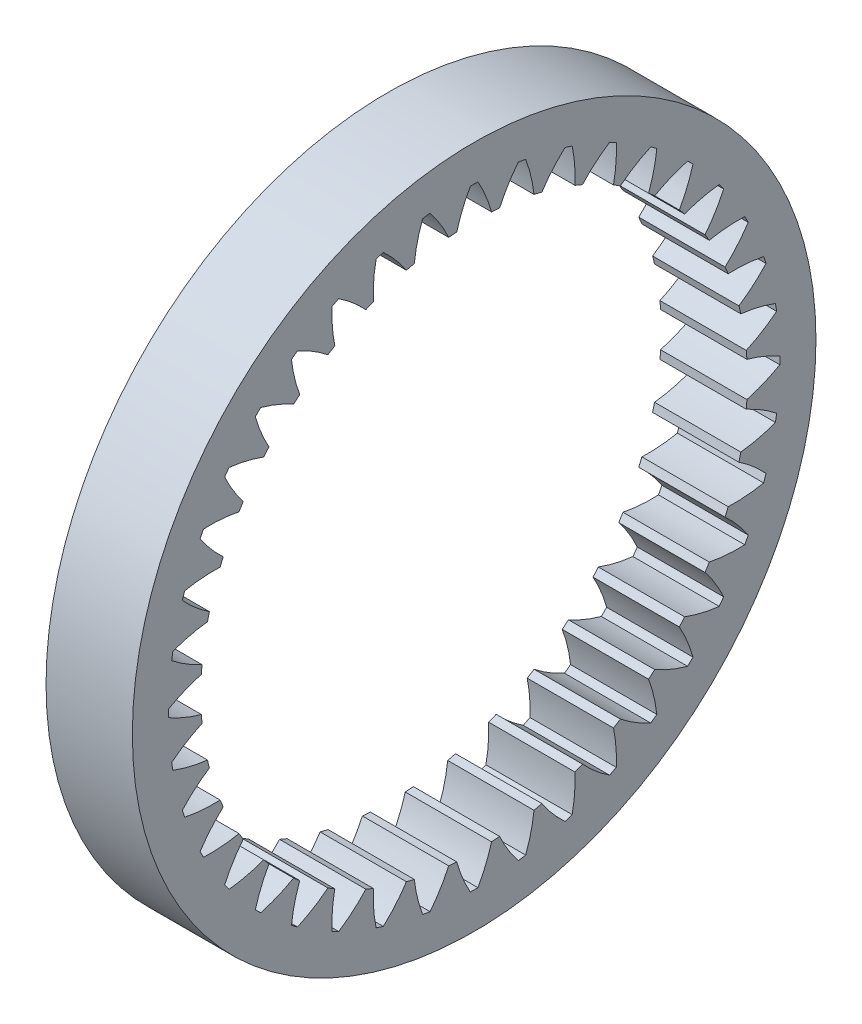
SolidWorks part; units mm, degrees
ref_plane "Plane1" through (0, 0, 0) normal (0, 0, 1) x (1, 0, 0)
ref_plane "Plane2" through (0, 0, 0) normal (0, 1, 0) x (1, 0, 0)
ref_plane "Plane3" through (0, 0, 0) normal (1, 0, 0) x (0, 0, -1)
sketch "HoldingSke" plane through (0, 0, 0) normal (0, 1, 0) x (1, 0, 0)
  line L0 (0, 0) -> (0.383, -0.3214)
  line L1 (-15, 0) -> (100, 0) construction
  line L2 (0, 0) -> (-2.1039, 2.3779)
  line L3 (0, 0) -> (-11.863, 4.5341)
  line L4 (0, 0) -> (6.6156, 5.5511)
  line L5 (0, 0) -> (-23.7986, -8.8762)
  line L6 (0, 0) -> (-10.5278, -7.1032)
  line L7 (-2.1039, 2.3779) -> (3.3635, 27.1825)
  line L8 (-76.2, 4.3779) -> (-54.61, 4.3779)
  line L9 (-71.009, 38.7566) -> (-53.1078, 45.2721)
  line L10 (-76.2, 71.12) -> (104.1128, 71.12)
  line L11 (0, 0) -> (-12, 0)
  line L12 (-76.2, 101.6) -> (-76.133, 101.6)
  line L13 (24.9733, 27.94) -> (52.9518, 28.4284)
  line L14 (24.9733, 27.94) -> (24.9743, 27.94)
  line L15 (24.9733, 27.94) -> (100.4006, 29.5858)
  circle A0 centre (0, 0) radius 12.5
  circle A1 centre (0, 0) radius 12.7
  circle A2 centre (0, 0) radius 12.7
  dimension "MHD" = 25.4
  dimension "Hub_dia" = 25.4
  dimension "Diameter" = 25
  dimension "Num_teeth" = 40
  dimension "Pitch" = 0.5
  dimension "Overall_len" = 25.4
  dimension "Show_teeth" = 40
  dimension "Thickness" = 12.7
  dimension "OAL" = 25.4001
  dimension "T_dim" = 21.59
  dimension "Ap" = 20
  dimension "H" = 19.05
  dimension "Pitch_radius" = 180.3128
  dimension "Width" = 12
  dimension "Backlash" = 0.067
  dimension "Addendum_fac" = 1
  dimension "Dedendum_fac" = 1.25
  dimension "Clearance_fac" = 0.25
  dimension "Dedendum_add" = 0.001
  dimension "Module" = 2
sketch "BasProSke" plane through (0, 0, 0) normal (0, 1, 0) x (1, 0, 0)
  line L0 (-10, 0) -> (60, 0) construction
  line L1 (0, 38) -> (0, 42.5264)
  line L2 (0, 38) -> (12, 38)
  line L3 (12, 38) -> (12, 42.5264)
  line L4 (12, 42.5264) -> (0, 42.5264)
  dimension "Thickness" = 12
  dimension "Diameter" = 85.0528
  dimension "Inside_diameter" = 76
revolve "Base-Revolve" add sketch "BasProSke" angle 360 about L0
sketch "TooCutSke" plane through (0, 0, 0) normal (1, 0, 0) x (0, 0, -1)
  line L3 (1.7379, 39.9622) -> (1.7379, 53.6633) construction
  line L4 (0, 0) -> (0, 59.563) construction
  line L5 (0, 0) -> (-5.3609, 68.1169) construction
  line L6 (-16.8604, 32.6066) -> (35.072, 36.6938) construction
  circle A0 centre (0, 0) radius 40 construction
  circle A1 centre (0, 0) radius 42.501 construction
  circle A2 centre (0, 0) radius 33.8289 construction
  circle A3 centre (0, 0) radius 37.9746 construction
  arc A4 (2.4273, 37.8969) -> (0.5225, 42.4978) centre (-16.8604, 32.6066) ccw
  arc A5 (2.4273, 37.8969) -> (-2.4273, 37.8969) centre (0, 0) ccw
  arc A6 (0.5225, 42.4978) -> (-0.5225, 42.4978) centre (0, 0) ccw
  arc A7 (-0.5225, 42.4978) -> (-2.4273, 37.8969) centre (16.8604, 32.6066) ccw
  dimension "Pitch_dia" = 80
  dimension "Base_dia" = 67.6579
  dimension "Root_dia" = 85.002
  dimension "Overcut_dia" = 75.9492
  dimension "Flank_rad" = 20
  dimension "Half_ang" = 4.5
  dimension "Half_CT" = 1.7379
extrude "ToothCut" cut sketch "TooCutSke" along normal through all
fillet "Breaks" [suppressed] radius 0.2
fillet "RootFillets" [suppressed] radius 0.501
pattern_circular "TeethCuts" count 40 every 9 about axis through (-10, 0, 0) along (1, 0, 0) of "RootFillets", "Breaks", "ToothCut"
sketch "Sketch1" plane through (12, 0, 0) normal (1, 0, 0) x (0, 0, -1)
  circle A0 centre (0, 0) radius 42.5264
  circle A1 centre (0, 0) radius 47.5264
  dimension "D1" = 5
extrude "Boss-Extrude1" add sketch "Sketch1" against normal through all
equation "' \"Module@HoldingSke\" = 6.35"
equation "' \"Num_teeth@HoldingSke\" = 24"
equation "' \"Ap@HoldingSke\" =  14.5"
equation "' \"Ap@HoldingSke\" = 14.5"
equation "' \"Width@HoldingSke\" = 12"
equation "' \"Diameter@HoldingSke\" = 8 * 25.4"
equation "' \"Show_teeth@HoldingSke\" = 100"
equation "' \"Backlash@HoldingSke\" = 0.009 * 25.4"
equation "' \"Addendum_fac@HoldingSke\" = 1.0"
equation "' \"Dedendum_fac@HoldingSke\" = 1.25"
equation "' \"Dedendum_add@HoldingSke\" = 0.00005 * 25.4"
equation "' \"Clearance_fac@HoldingSke\" = 0.25"
equation "\"Pitch@HoldingSke\" = 1 / \"Module@HoldingSke\" "
equation "\"Overcut_dia@TooCutSke\" = (\"Num_teeth@HoldingSke\" - 2 * \"Addendum_fac@HoldingSke\") / \"Pitch@HoldingSke\" - 0.002 * 25.4"
equation "\"Pitch_dia@TooCutSke\" = \"Num_teeth@HoldingSke\" / \"Pitch@HoldingSke\""
equation "\"Base_dia@TooCutSke\" = \"Num_teeth@HoldingSke\" / \"Pitch@HoldingSke\" * cos((\"Ap@HoldingSke\"  * 3.14159265 / 180)) * 0.90"
equation "\"Root_dia@TooCutSke\" = \"Num_teeth@HoldingSke\"  / \"Pitch@HoldingSke\" + 2 *  \"Dedendum_fac@HoldingSke\"/ \"Pitch@HoldingSke\" + \"Dedendum_add@HoldingSke\" * 2"
equation "\"Half_ang@TooCutSke\" = 180 / \"Num_teeth@HoldingSke\""
equation "\"Half_CT@TooCutSke\" = \"Num_teeth@HoldingSke\" / \"Pitch@HoldingSke\" * sin((3.14159265 / 2 / \"Num_teeth@HoldingSke\")) / 2 + 10 * \"Backlash@HoldingSke\" / 4"
equation "\"Flank_rad@TooCutSke\" = \"Num_teeth@HoldingSke\" / \"Pitch@HoldingSke\" / 4"
equation "\"Radius@RootFillets\"= \"Clearance_fac@HoldingSke\" / \"Pitch@HoldingSke\" + \"Dedendum_add@HoldingSke\""
equation "\"Break_rad@Breaks\" = 0.02 / \"Pitch@HoldingSke\" * 5"
equation "\"Num_teeth@TeethCuts\" = int( \"Show_teeth@HoldingSke\" ) + 1"
equation "\"Num_teeth@TeethCuts\" = ((sgn( \"Num_teeth@TeethCuts\" - \"Num_teeth@HoldingSke\" )-1)*( \"Num_teeth@TeethCuts\" - \"Num_teeth@HoldingSke\" ))/-2+ \"Num_teeth@HoldingSke\""
equation "\"Num_teeth@TeethCuts\" = ((sgn( \"Num_teeth@TeethCuts\" - 2.0)+1)*( \"Num_teeth@TeethCuts\" - 2.0))/2 +2.0"
equation "\"Angle@TeethCuts\" = 360.0 / \"Num_teeth@HoldingSke\""
equation "\"Diameter@BasProSke\" = \"Num_teeth@HoldingSke\"  / \"Pitch@HoldingSke\" + 2 *  \"Dedendum_fac@HoldingSke\"/ \"Pitch@HoldingSke\" + \"Dedendum_add@HoldingSke\" * 2 + 0.002 * 25.4"
equation "\"Diameter@BasProSke\" = ((sgn( \"Diameter@BasProSke\"  - \"Diameter@HoldingSke\" )+1)*( \"Diameter@BasProSke\"  - \"Diameter@HoldingSke\" ))/2 + \"Diameter@HoldingSke\""
equation "\"Inside_diameter@BasProSke\" =  (\"Num_teeth@HoldingSke\" - 2 * \"Addendum_fac@HoldingSke\") / \"Pitch@HoldingSke\" "
equation "\"Thickness@BasProSke\"  = \"Width@HoldingSke\""
